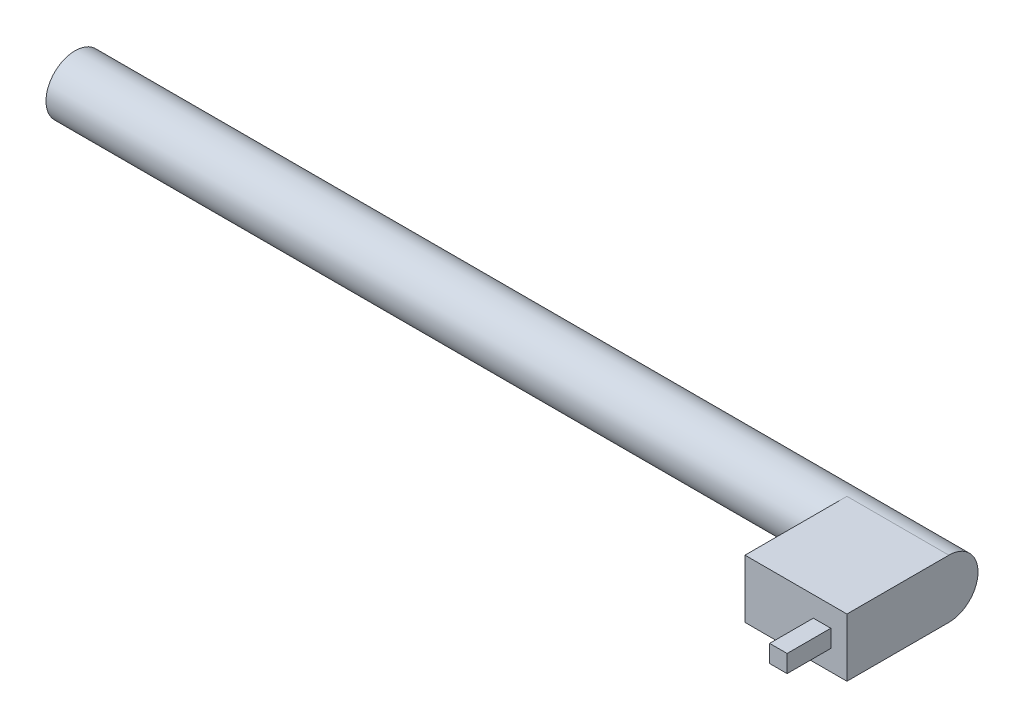
SolidWorks part; units mm, degrees
ref_plane "前视基准面" through (0, 0, 0) normal (0, 0, 1) x (1, 0, 0)
ref_plane "上视基准面" through (0, 0, 0) normal (0, 1, 0) x (1, 0, 0)
ref_plane "右视基准面" through (0, 0, 0) normal (1, 0, 0) x (0, 0, -1)
other "Configuration Table"
sketch "草图1" plane through (0, 0, 0) normal (1, 0, 0) x (0, 0, -1)
  circle A0 centre (0, 0) radius 10
  dimension "D1" = 20
extrude "凸台-拉伸1" add sketch "草图1" along normal mid plane 300
sketch "草图2" plane through (0, 0, 0) normal (0, 0, 1) x (1, 0, 0)
  line L0 (150, 10) -> (-150, 10) construction
  line L1 (150, -10) -> (115, -10)
  line L2 (150, -10) -> (150, 10)
  line L3 (150, 10) -> (115, 10)
  line L4 (115, -10) -> (115, 10)
  dimension "D1" = 35
extrude "凸台-拉伸2" add sketch "草图2" along normal blind 35
sketch "草图3" plane through (0, 0, 35) normal (0, 0, 1) x (1, 0, 0)
  line L0 (150, -10) -> (150, 10) construction
  line L1 (138.4586, -3) -> (144.4586, -3)
  line L2 (138.4586, -3) -> (138.4586, 3)
  line L3 (138.4586, 3) -> (144.4586, 3)
  line L4 (144.4586, -3) -> (144.4586, 3)
  line L5 (138.4586, -3) -> (144.4586, 3) construction
  line L6 (138.4586, 3) -> (144.4586, -3) construction
  line L7 (150, 10) -> (115, 10) construction
  circle A0 centre (141.4586, 0) radius 0.5
  point P6 (0, 0)
  dimension "D1" = 1
  dimension "D2" = 6
  dimension "D3" = 8.5414
  dimension "D4" = 10
  dimension "D5" = 6
extrude "凸台-拉伸3" add sketch "草图3" along normal blind 15 contours L1 L4 L3 L2 A0 | A0
